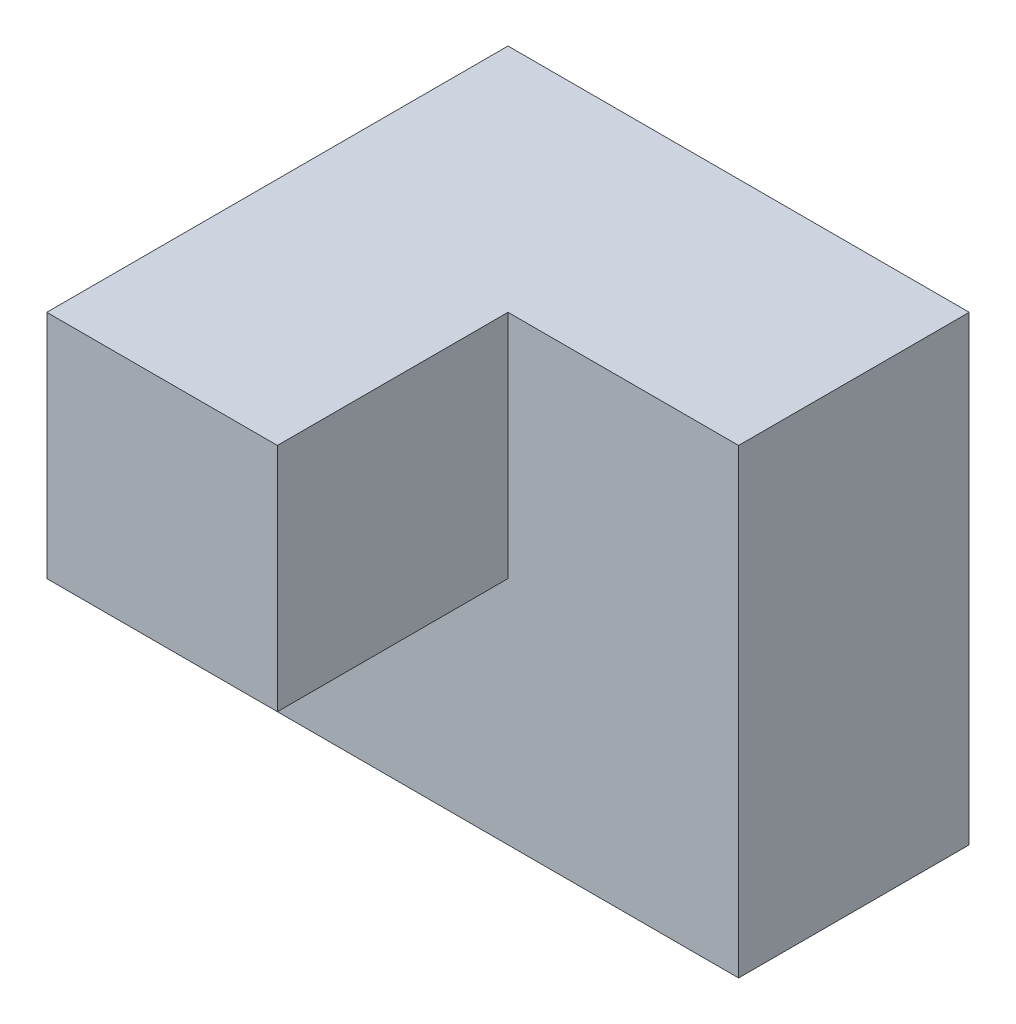
SolidWorks part; units mm, degrees
ref_plane "Front Plane" through (0, 0, 0) normal (0, 0, 1) x (1, 0, 0)
ref_plane "Top Plane" through (0, 0, 0) normal (0, 1, 0) x (1, 0, 0)
ref_plane "Right Plane" through (0, 0, 0) normal (1, 0, 0) x (0, 0, -1)
sketch "Sketch1" plane through (0, 0, 0) normal (0, 0, 1) x (1, 0, 0)
  line L0 (0, 0) -> (38.1, 0)
  line L1 (38.1, 0) -> (38.1, -38.1)
  line L2 (38.1, -38.1) -> (0, -38.1)
  line L3 (0, -38.1) -> (0, 0)
  dimension "D1" = 38.1
  dimension "D2" = 38.1
extrude "Boss-Extrude1" add sketch "Sketch1" along normal blind 19.05
sketch "Sketch2" plane through (0, 0, 19.05) normal (0, 0, 1) x (1, 0, 0)
  line L0 (0, -19.05) -> (19.05, -19.05)
  line L1 (0, 0) -> (0, -38.1) construction
  line L2 (19.05, -19.05) -> (19.05, 0)
  line L3 (38.1, 0) -> (0, 0) construction
  line L4 (0, -19.05) -> (0, 0)
  line L5 (0, 0) -> (19.05, 0)
  dimension "D1" = 19.05
  dimension "D2" = 19.05
extrude "Boss-Extrude2" add sketch "Sketch2" along normal blind 19.05
